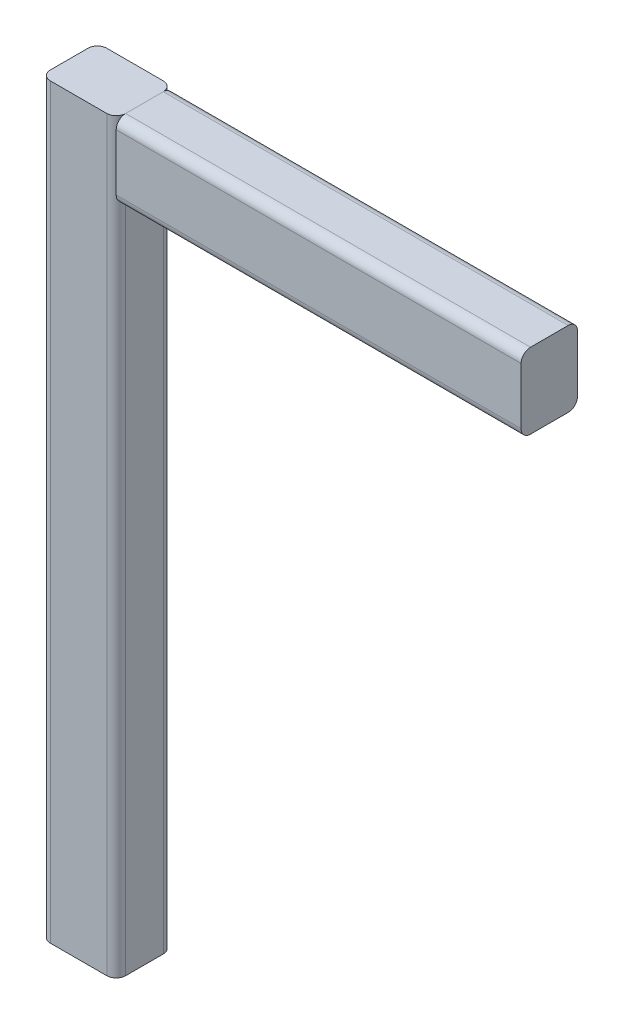
SolidWorks part; units mm, degrees
ref_plane "Front Plane" through (0, 0, 0) normal (0, 0, 1) x (1, 0, 0)
ref_plane "Top Plane" through (0, 0, 0) normal (0, 1, 0) x (1, 0, 0)
ref_plane "Right Plane" through (0, 0, 0) normal (1, 0, 0) x (0, 0, -1)
other "Configuration Table"
sketch "Sketch1" plane through (0, 0, 0) normal (0, 0, 1) x (1, 0, 0)
  line L1 (0, 0) -> (-80, 0)
  line L2 (0, 0) -> (0, -793.1395)
  line L3 (0, -793.1395) -> (-80, -793.1395)
  line L4 (-80, 0) -> (-80, -793.1395)
  dimension "D1" = 80
extrude "Boss-Extrude1" add sketch "Sketch1" against normal blind 60
sketch "Sketch2" plane through (0, 0, 0) normal (1, 0, 0) x (0, 0, -1)
  line L0 (60, -793.1395) -> (60, 0) construction
  line L1 (0, 0) -> (60, 0)
  line L2 (0, 0) -> (0, -80)
  line L3 (0, -80) -> (60, -80)
  line L4 (60, 0) -> (60, -80)
  dimension "D1" = 80
extrude "Boss-Extrude2" add sketch "Sketch2" along normal blind 430 separate body
fillet "Fillet1" radius 10 4 edges at (-80, -396.5698, 0) (0, -396.5698, 0) (-80, -396.5698, -60) (0, -396.5698, -60)
fillet "Fillet2" radius 10 4 edges at (215, -80, -60) (215, 0, -60) (215, -80, 0) (215, 0, 0)
